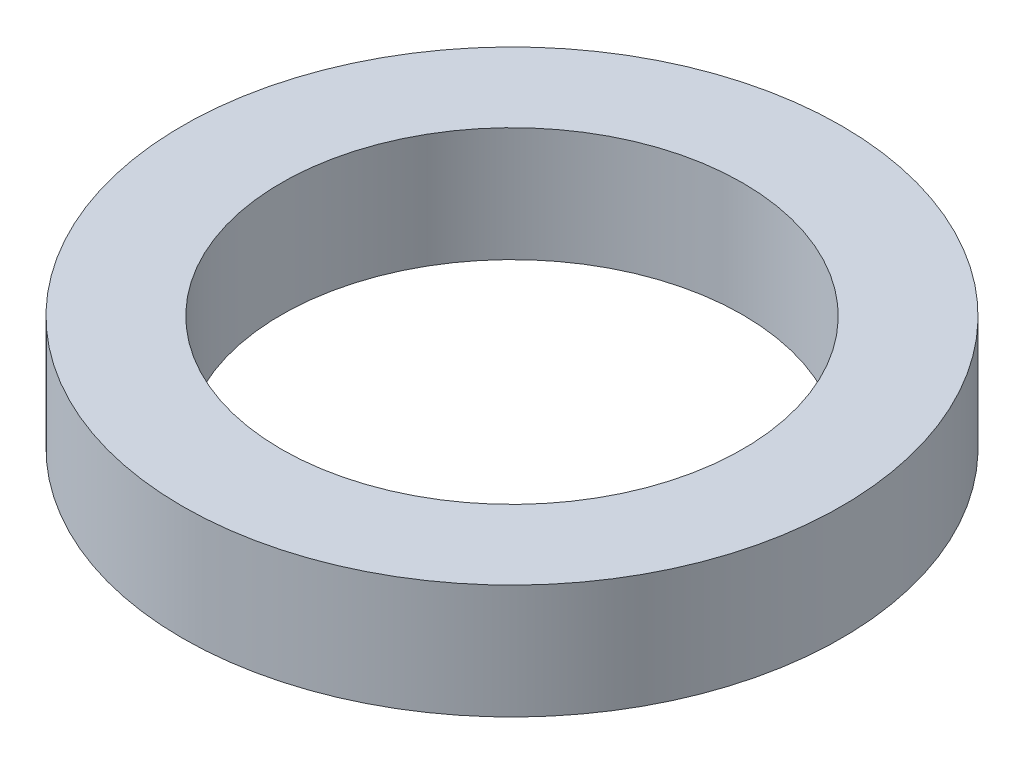
SolidWorks part; units mm, degrees
material "ABS"
ref_plane "Front Plane" through (0, 0, 0) normal (0, 0, 1) x (1, 0, 0)
ref_plane "Top Plane" through (0, 0, 0) normal (0, 1, 0) x (1, 0, 0)
ref_plane "Right Plane" through (0, 0, 0) normal (1, 0, 0) x (0, 0, -1)
sketch "Sketch1" plane through (0, 0, 0) normal (0, 1, 0) x (1, 0, 0)
  circle A0 centre (0, 0) radius 2.667
  circle A1 centre (0, 0) radius 3.81
  dimension "D1" = 5.334
  dimension "D2" = 7.62
extrude "Boss-Extrude1" add sketch "Sketch1" along normal blind 1.3208
